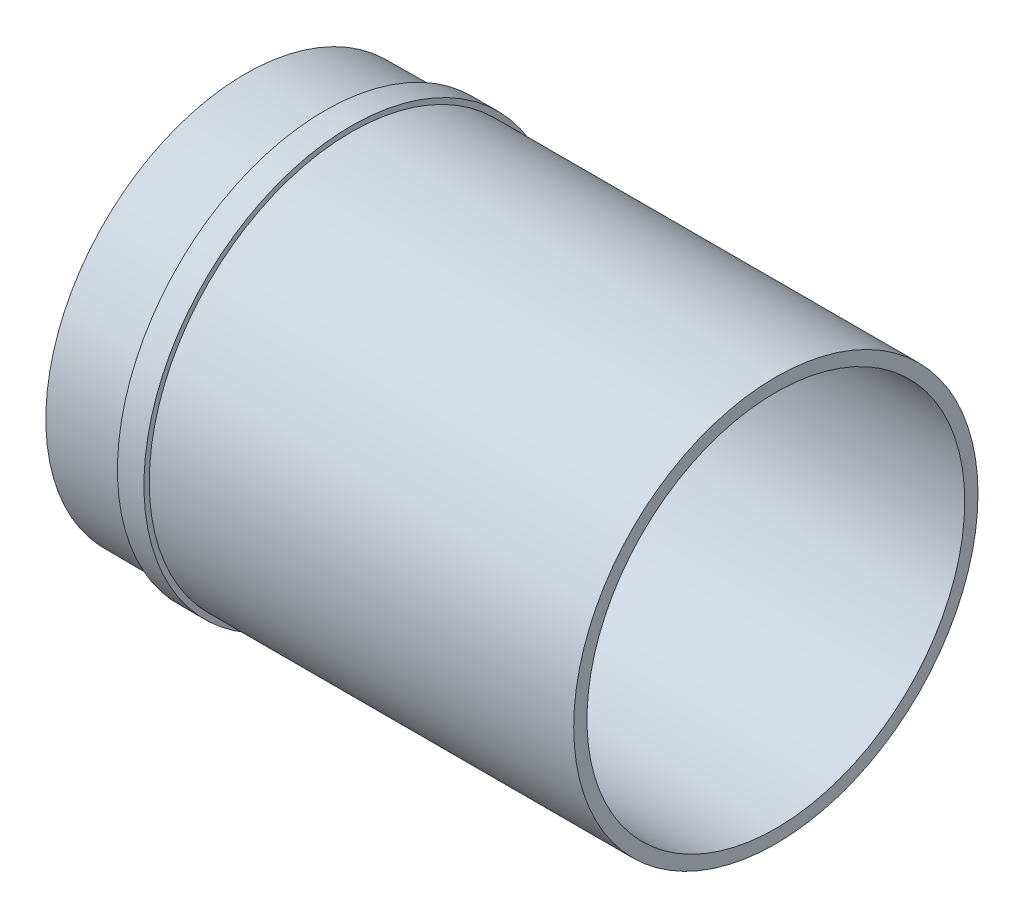
SolidWorks part; units mm, degrees
material "Thornel VCB-20 Carbon Cloth"
ref_plane "Front Plane" through (0, 0, 0) normal (0, 0, 1) x (1, 0, 0)
ref_plane "Top Plane" through (0, 0, 0) normal (0, 1, 0) x (1, 0, 0)
ref_plane "Right Plane" through (0, 0, 0) normal (1, 0, 0) x (0, 0, -1)
sketch "Sketch1" plane through (0, 0, 0) normal (0, 0, 1) x (1, 0, 0)
  line L0 (0, 0) -> (0, 3483.1) construction
  line L1 (0, 3635.5) -> (0, 3633.5)
  line L2 (0, 3557.2968) -> (-750, 3557.2968) construction
  line L3 (0, 3633.5) -> (0, 3635.5) construction
  line L4 (0, 3633.5) -> (160, 3633.5)
  line L5 (-5, 3628.5) -> (160, 3628.5)
  line L6 (-5, 3630.4966) -> (-5, 3628.5)
  line L7 (-750, 3557.2968) -> (-725.3758, 3557.2968)
  line L8 (160, 3633.5) -> (160, 3628.5)
  line L9 (-650, 3576.9205) -> (-650, 3571.8385)
  line L10 (-650, 3571.8385) -> (-600, 3571.8385)
  line L11 (-600, 3571.8385) -> (-600, 3580.5768)
  line L12 (-2.5, 3631) -> (157.5, 3631) construction
  line L13 (-2.5, 3631) -> (157.5, 3631) construction
  line L14 (-725.628, 3559.7968) -> (-725.628, 3559.7968)
  line L15 (-500, 3598.4287) -> (-500, 3595.9046)
  line L18 (157.5, 3631) -> (157.5, 3631)
  line L21 (-2.5, 3632.9991) -> (-2.5, 3631) construction
  line L22 (-2.5, 3632.9991) -> (-2.5, 3631) construction
  line L23 (-470, 3604.991) -> (-470, 3602.4698)
  line L24 (-320, 3621.3893) -> (-320, 3618.8795)
  line L25 (-350, 3616.1014) -> (-350, 3613.5897)
  line L26 (-40, 3632.7798) -> (-40, 3630.2796)
  line L27 (-10, 3632.9862) -> (-10, 3635.4862)
  line L28 (-170, 3629.0204) -> (-170, 3631.5231)
  line L29 (-200, 3627.4907) -> (-200, 3624.9869)
  line L30 (-40, 3630.2796) -> (-40, 3628.5)
  line L31 (-40, 3628.5) -> (-5, 3628.5)
  line L32 (-10, 3632.9862) -> (-10, 3632.6862)
  line L33 (-170, 3629.0204) -> (-170, 3628.7201)
  line L34 (-320, 3618.8795) -> (-320, 3618.5784)
  line L35 (-470, 3602.4698) -> (-470, 3602.1673)
  arc A0 (0, 3635.5) -> (-750, 3557.2968) centre (0, 0) ccw
  arc A1 (-5, 3630.4966) -> (-600, 3580.5768) centre (0, 0) ccw
  arc A2 (-5, 3630.4966) -> (-748.9685, 3552.4043) centre (0, 0) ccw construction
  arc A5 (-650, 3571.8385) -> (-725.3758, 3557.2968) centre (0, 0) ccw
  arc A6 (-5, 3630.4966) -> (-725.3758, 3557.2968) centre (0, 0) ccw construction
  arc A7 (-2.5, 3632.9991) -> (-725.628, 3559.7968) centre (0, 0) ccw construction
  arc A8 (-2.5, 3632.9991) -> (-725.628, 3559.7968) centre (0, 0) ccw construction
  arc A9 (-500, 3598.4287) -> (-470, 3602.4698) centre (0, 0) cw
  arc A10 (-350, 3616.1014) -> (-320, 3618.8795) centre (0, 0) cw
  arc A11 (-10, 3632.9862) -> (-40, 3632.7798) centre (0, 0) ccw
  arc A12 (-170, 3629.0204) -> (-200, 3627.4907) centre (0, 0) ccw
  arc A13 (-40, 3632.4798) -> (-10, 3632.6862) centre (0, 0) cw
  arc A14 (-200, 3627.1903) -> (-170, 3628.7201) centre (0, 0) cw
  arc A15 (-350, 3615.8) -> (-320, 3618.5784) centre (0, 0) cw
  arc A16 (-500, 3598.1258) -> (-470, 3602.1673) centre (0, 0) cw
  dimension "D1" = 7271
  dimension "D7" = 100
  dimension "D10" = 30
  dimension "D8" = 3633
  dimension "D12" = 3633
  dimension "D15" = 3633
  dimension "D18" = 3633
  dimension "D21" = 3632.7
  dimension "D23" = 3632.7
  dimension "D22" = 3632.7
  dimension "D24" = 3632.7
  dimension "D2" = 152.4
  dimension "D3" = 750
  dimension "D4" = 2
  dimension "D5" = 160
  dimension "D9" = 50
  dimension "D11" = 180
  dimension "D13" = 30
  dimension "D14" = 180
  dimension "D16" = 30
  dimension "D17" = 200
  dimension "D19" = 30
  dimension "D20" = 180
  dimension "D6" = 5
revolve "Revolve1" add sketch "Sketch1" angle 360 about L2
